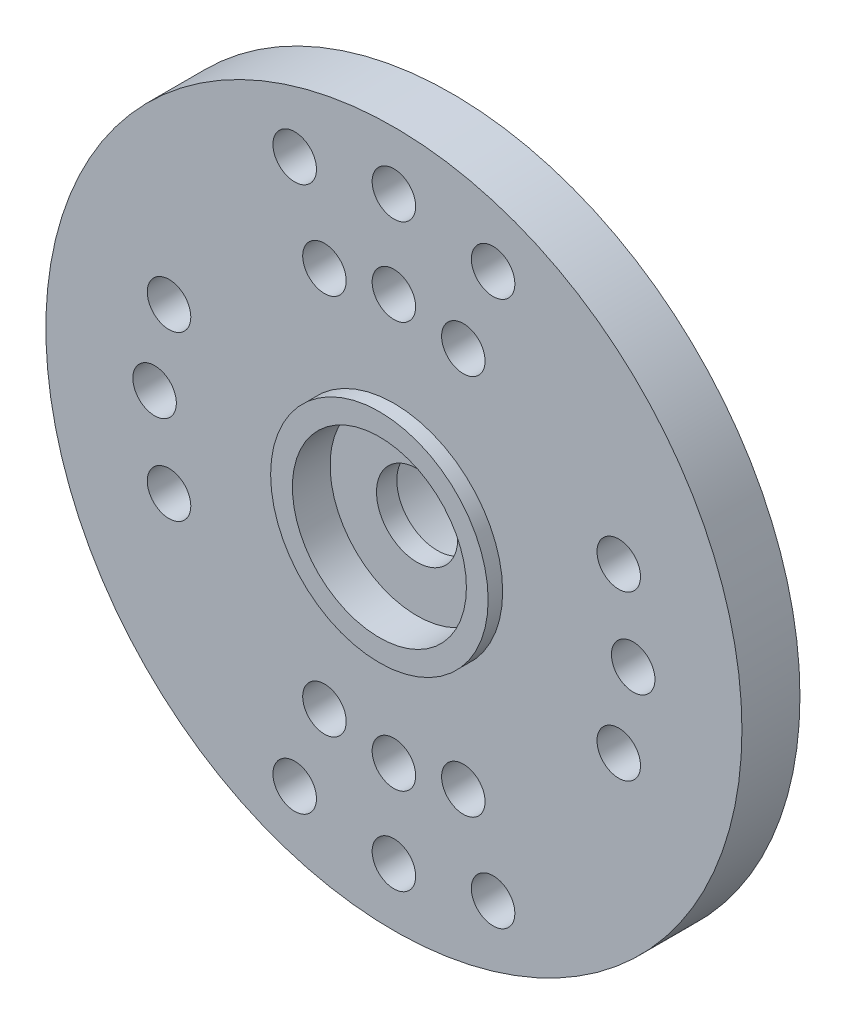
SolidWorks part; units mm, degrees
material "Полибутадиен (PB)"
ref_plane "Спереди" through (0, 0, 0) normal (0, 0, 1) x (1, 0, 0)
ref_plane "Сверху" through (0, 0, 0) normal (0, 1, 0) x (1, 0, 0)
ref_plane "Справа" through (0, 0, 0) normal (1, 0, 0) x (0, 0, -1)
sketch "Эскиз1" plane through (0, 0, 0) normal (1, 0, 0) x (0, 0, -1)
  line L0 (0, 3.75) -> (0, 12)
  line L1 (0, 12) -> (2, 12)
  line L2 (2, 12) -> (2, 4.5)
  line L3 (2, 4.5) -> (4.5, 4.5)
  line L4 (4.5, 4.5) -> (4.5, 3)
  line L5 (4.5, 3) -> (1.5, 3)
  line L6 (-0.5, 3.75) -> (0, 3.75)
  line L7 (-0.5, 3.75) -> (-0.5, 3)
  line L8 (-0.5, 3) -> (0.8, 3)
  line L9 (0.8, 3) -> (0.8, 1.4)
  line L10 (0.8, 1.4) -> (1.5, 1.4)
  line L11 (1.5, 3) -> (1.5, 1.4)
  line L12 (1.5, 1.4) -> (1.5869, 1.4053)
  dimension "D1" = 2
  dimension "D2" = 3
  dimension "D3" = 12
  dimension "D4" = 4.5
  dimension "D5" = 3
  dimension "D6" = 3.75
  dimension "D7" = 3
  dimension "D8" = 0.5
  dimension "D9" = 4.5
  dimension "D10" = 1.3
  dimension "D11" = 1.4
ref_axis "Ось1" through (0, 0, 50) along (0, 0, -1)
revolve "Повернуть1" add sketch "Эскиз1" angle 360 about axis through (0, 0, 50) along (0, 0, -1)
sketch "Эскиз2" plane through (0, 0, 0) normal (0, 0, 1) x (1, 0, 0)
  line L0 (0, 0) -> (8.25, 0) construction
  line L1 (0, 0) -> (7.7525, -2.8217) construction
  line L2 (0, 0) -> (0, 7) construction
  line L3 (0, 0) -> (2.3941, 6.5778) construction
  line L4 (0, 0) -> (0, 7) construction
  line L5 (0, 0) -> (-2.3941, 6.5778) construction
  circle A0 centre (8.25, 0) radius 0.75
  circle A1 centre (7.7525, -2.8217) radius 0.75
  circle A2 centre (7.7525, 2.8217) radius 0.75
  circle A3 centre (-8.25, 0) radius 0.75
  circle A4 centre (-7.7525, -2.8217) radius 0.75
  circle A5 centre (-7.7525, 2.8217) radius 0.75
  circle A6 centre (0, 7) radius 0.75
  circle A8 centre (0, 10) radius 0.75
  circle A9 centre (2.3941, 6.5778) radius 0.75
  circle A10 centre (3.4202, 9.3969) radius 0.75
  circle A11 centre (-2.3941, 6.5778) radius 0.75
  circle A12 centre (-3.4202, 9.3969) radius 0.75
  circle A13 centre (0, -7) radius 0.75
  circle A14 centre (0, -10) radius 0.75
  circle A15 centre (3.4202, -9.3969) radius 0.75
  circle A16 centre (2.3941, -6.5778) radius 0.75
  circle A17 centre (-2.3941, -6.5778) radius 0.75
  circle A18 centre (-3.4202, -9.3969) radius 0.75
  point P12 (0, 0)
  point P20 (0, 0)
  point P51 (0, 0)
  dimension "D1" = 1.5
  dimension "D7" = 1.5
  dimension "D9" = 1.5
  dimension "D2" = 8.25
  dimension "D4" = 20
  dimension "D8" = 7
  dimension "D10" = 10
  dimension "D12" = 20
  dimension "D14" = 20
  dimension "D3" = 2
  dimension "D5" = 2
  dimension "D6" = 2
  dimension "D11" = 2
  dimension "D13" = 2
  dimension "D15" = 2
extrude "Вырез-Вытянуть1" cut sketch "Эскиз2" against normal through all
